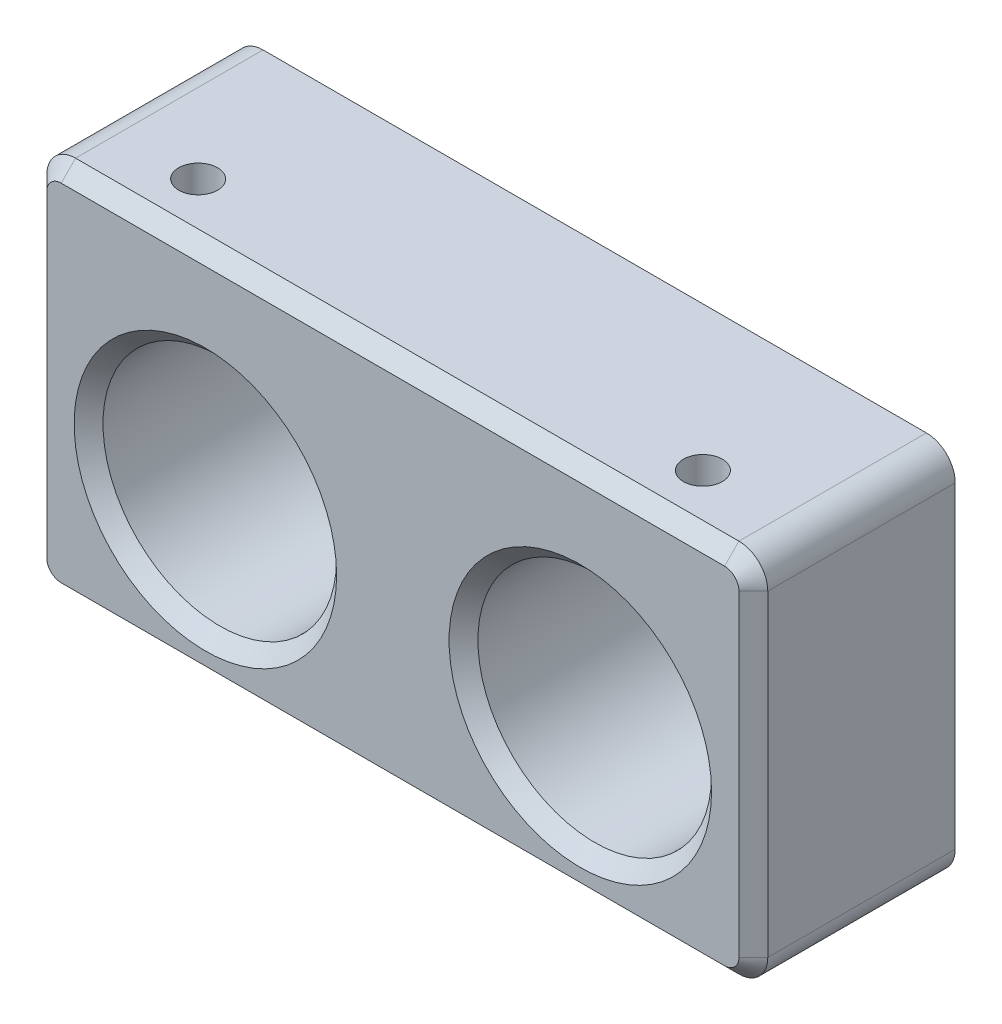
SolidWorks part; units mm, degrees
ref_plane "前视基准面" through (0, 0, 0) normal (0, 0, 1) x (1, 0, 0)
ref_plane "上视基准面" through (0, 0, 0) normal (0, 1, 0) x (1, 0, 0)
ref_plane "右视基准面" through (0, 0, 0) normal (1, 0, 0) x (0, 0, -1)
sketch "草图1" plane through (0, 0, 0) normal (0, 0, 1) x (1, 0, 0)
  line L0 (-13, 0) -> (13, 0) construction
  line L1 (-25, 15) -> (25, 15)
  line L2 (-25, 15) -> (-25, -11)
  line L3 (-25, -11) -> (25, -11)
  line L4 (25, 15) -> (25, -11)
  circle A0 centre (13, 0) radius 8.1
  circle A1 centre (-13, 0) radius 8.1
  point P9 (0, 15)
  point P10 (23.4196, -11.9093)
  dimension "D2" = 16.2
  dimension "D1" = 15
  dimension "D3" = 26
  dimension "D4" = 50
  dimension "D5" = 11
extrude "凸台-拉伸1" add sketch "草图1" along normal blind 14
sketch "草图2" plane through (0, 15, 0) normal (0, 1, 0) x (1, 0, 0)
  line L1 (25, -14) -> (-25, -14) construction
  circle A0 centre (-17.5, -10) radius 1.35
  circle A1 centre (17.5, -10) radius 1.35
  point P2 (0, 0)
  dimension "D1" = 17.5
  dimension "D2" = 2.7
  dimension "D3" = 4
  dimension "D4" = 35
extrude "切除-拉伸1" cut sketch "草图2" against normal blind 5
sketch "草图3" plane through (0, 0, 0) normal (0, 0, -1) x (-1, 0, 0)
  line L0 (25, -11) -> (-25, -11) construction
  line L1 (-6, 11) -> (6, 11)
  line L2 (-6, 11) -> (-6, 7)
  line L3 (-6, 7) -> (6, 7)
  line L4 (6, 11) -> (6, 7)
  line L5 (-6, -11) -> (6, -11)
  line L6 (-6, -11) -> (-6, -7)
  line L7 (-5, -6) -> (5, -6)
  line L8 (6, -11) -> (6, -7)
  arc A0 (-6, -7) -> (-5, -6) centre (-5, -7) cw
  arc A1 (5, -6) -> (6, -7) centre (5, -7) cw
  point P10 (0, -6)
  point P14 (-6, -6)
  point P17 (6, -6)
  point P18 (0, 7)
  dimension "D3" = 1
  dimension "D1" = 6
  dimension "D2" = 12
  dimension "D4" = 7
  dimension "D5" = 12
  dimension "D6" = 4
extrude "切除-拉伸2" cut sketch "草图3" against normal blind 4
chamfer "倒角1" distance 1 angle 45 2 edges at (21.1, 0, 14) (-4.9, 0, 14)
fillet "圆角1" radius 2 4 edges at (-25, 15, 7) (25, 15, 7) (25, -11, 7) (-25, -11, 7)
chamfer "倒角2" distance 1 angle 45 8 edges at (0, 15, 14) (-24.4142, 14.4142, 14) (24.4142, 14.4142, 14) (-25, 2, 14) (25, 2, 14) (-24.4142, -10.4142, 14) (24.4142, -10.4142, 14) (0, -11, 14)
